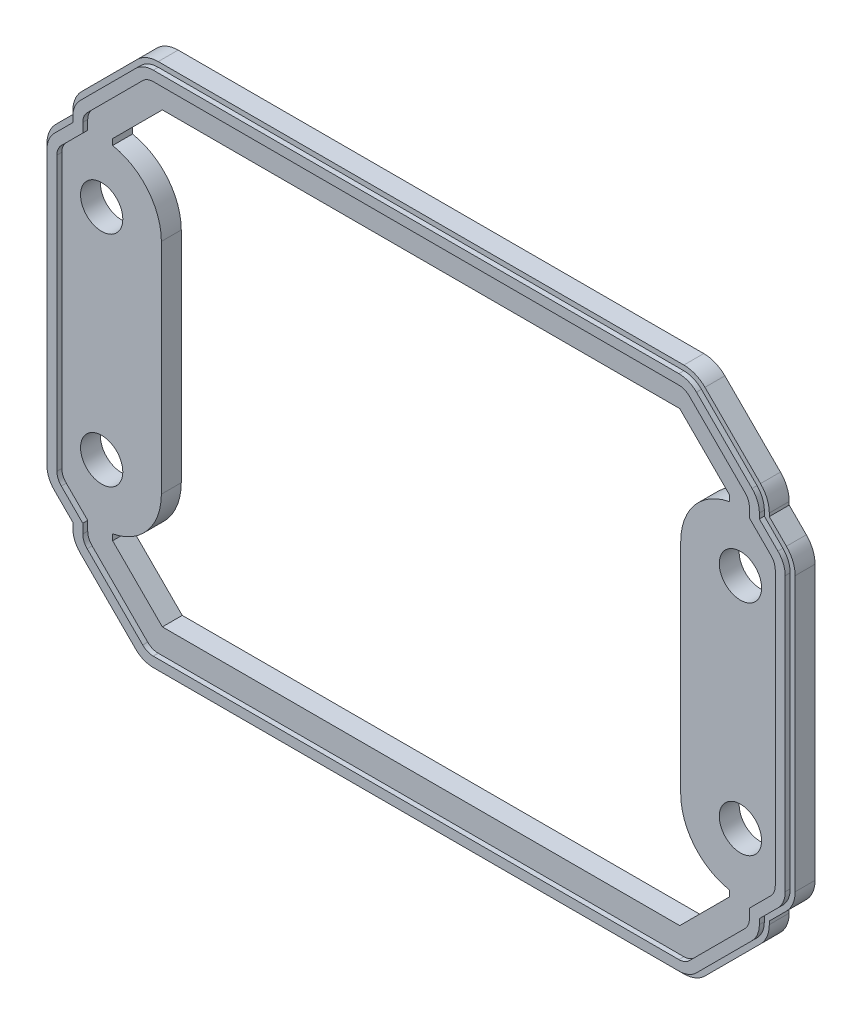
SolidWorks part; units mm, degrees
ref_plane "Front Plane" through (0, 0, 0) normal (0, 0, 1) x (1, 0, 0)
ref_plane "Top Plane" through (0, 0, 0) normal (0, 1, 0) x (1, 0, 0)
ref_plane "Right Plane" through (0, 0, 0) normal (1, 0, 0) x (0, 0, -1)
sketch "Sketch1" plane through (0, 0, 0) normal (0, 0, 1) x (1, 0, 0)
  line L12 (-1.6569, 49) -> (-53.6569, 49)
  line L13 (3.3431, 44) -> (-1.6569, 49)
  line L14 (3.3431, 43.3983) -> (3.3431, 44)
  line L15 (-1.5569, 15.5) -> (-1.5569, 37.5)
  line L16 (-64.3782, 10.6213) -> (-62.6569, 8.9)
  line L17 (-62.6569, 8.9) -> (-62.6569, 8.5858)
  line L18 (-61.7782, 6.4645) -> (-56.1924, 0.8787)
  line L19 (-54.0711, 0) -> (-1.2426, 0)
  line L20 (0.8787, 0.8787) -> (6.4645, 6.4645)
  line L21 (7.3431, 8.5858) -> (7.3431, 8.9)
  line L22 (7.3431, 8.9) -> (9.0645, 10.6213)
  line L23 (9.9431, 12.7426) -> (9.9431, 40.2574)
  line L24 (9.0645, 42.3787) -> (7.3431, 44.1)
  line L25 (7.3431, 44.1) -> (7.3431, 44.4142)
  line L26 (6.4645, 46.5355) -> (0.8787, 52.1213)
  line L27 (-1.2426, 53) -> (-54.0711, 53)
  line L28 (-56.1924, 52.1213) -> (-61.7782, 46.5355)
  line L29 (-62.6569, 44.4142) -> (-62.6569, 44.1)
  line L30 (-62.6569, 44.1) -> (-64.3782, 42.3787)
  line L31 (-65.2569, 40.2574) -> (-65.2569, 12.7426)
  line L32 (-64.3782, 10.6213) -> (-62.6569, 8.9)
  line L33 (-62.6569, 8.9) -> (-62.6569, 8.5858)
  line L34 (-61.7782, 6.4645) -> (-56.1924, 0.8787)
  line L35 (-54.0711, 0) -> (-1.2426, 0)
  line L36 (0.8787, 0.8787) -> (6.4645, 6.4645)
  line L37 (7.3431, 8.5858) -> (7.3431, 8.9)
  line L38 (7.3431, 8.9) -> (9.0645, 10.6213)
  line L39 (9.9431, 12.7426) -> (9.9431, 40.2574)
  line L40 (9.0645, 42.3787) -> (7.3431, 44.1)
  line L41 (7.3431, 44.1) -> (7.3431, 44.4142)
  line L42 (6.4645, 46.5355) -> (0.8787, 52.1213)
  line L43 (-1.2426, 53) -> (-54.0711, 53)
  line L44 (-56.1924, 52.1213) -> (-61.7782, 46.5355)
  line L45 (-62.6569, 44.4142) -> (-62.6569, 44.1)
  line L46 (-62.6569, 44.1) -> (-64.3782, 42.3787)
  line L47 (-65.2569, 40.2574) -> (-65.2569, 12.7426)
  line L48 (3.3431, 9) -> (3.3431, 9.6017)
  line L49 (-1.6569, 4) -> (3.3431, 9)
  line L50 (-53.6569, 4) -> (-1.6569, 4)
  line L51 (-58.6569, 9) -> (-53.6569, 4)
  line L52 (-58.6569, 9.6017) -> (-58.6569, 9)
  line L53 (-53.7569, 37.5) -> (-53.7569, 15.5)
  line L54 (-58.6569, 44) -> (-58.6569, 43.3983)
  line L55 (-53.6569, 49) -> (-58.6569, 44)
  line L56 (-1.6569, 49) -> (-53.6569, 49)
  line L57 (3.3431, 44) -> (-1.6569, 49)
  line L58 (3.3431, 43.3983) -> (3.3431, 44)
  line L59 (-1.5569, 15.5) -> (-1.5569, 37.5)
  line L60 (3.3431, 9) -> (3.3431, 9.6017)
  line L61 (-1.6569, 4) -> (3.3431, 9)
  line L62 (-53.6569, 4) -> (-1.6569, 4)
  line L63 (-58.6569, 9) -> (-53.6569, 4)
  line L64 (-58.6569, 9.6017) -> (-58.6569, 9)
  line L65 (-53.7569, 37.5) -> (-53.7569, 15.5)
  line L66 (-58.6569, 44) -> (-58.6569, 43.3983)
  line L67 (-53.6569, 49) -> (-58.6569, 44)
  circle A1 centre (4.4431, 37.5) radius 2.125
  circle A2 centre (4.4431, 37.5) radius 2.125
  circle A3 centre (-59.7569, 37.5) radius 2.125
  circle A4 centre (-59.7569, 37.5) radius 2.125
  circle A5 centre (-59.7569, 15.5) radius 2.125
  circle A6 centre (-59.7569, 15.5) radius 2.125
  circle A7 centre (4.4431, 15.5) radius 2.125
  circle A8 centre (4.4431, 15.5) radius 2.125
  arc A12 (3.3431, 43.3983) -> (-1.5569, 37.5) centre (4.4431, 37.5) ccw
  arc A13 (-1.5569, 15.5) -> (3.3431, 9.6017) centre (4.4431, 15.5) ccw
  arc A14 (-58.6569, 9.6017) -> (-53.7569, 15.5) centre (-59.7569, 15.5) ccw
  arc A15 (-53.7569, 37.5) -> (-58.6569, 43.3983) centre (-59.7569, 37.5) ccw
  arc A16 (3.3431, 43.3983) -> (-1.5569, 37.5) centre (4.4431, 37.5) ccw
  arc A17 (-1.5569, 15.5) -> (3.3431, 9.6017) centre (4.4431, 15.5) ccw
  arc A18 (-58.6569, 9.6017) -> (-53.7569, 15.5) centre (-59.7569, 15.5) ccw
  arc A19 (-53.7569, 37.5) -> (-58.6569, 43.3983) centre (-59.7569, 37.5) ccw
  arc A56 (9.0645, 10.6213) -> (9.9431, 12.7426) centre (6.9431, 12.7426) ccw
  arc A57 (9.0645, 10.6213) -> (9.9431, 12.7426) centre (6.9431, 12.7426) ccw
  arc A58 (9.9431, 40.2574) -> (9.0645, 42.3787) centre (6.9431, 40.2574) ccw
  arc A59 (9.9431, 40.2574) -> (9.0645, 42.3787) centre (6.9431, 40.2574) ccw
  arc A60 (7.3431, 44.4142) -> (6.4645, 46.5355) centre (4.3431, 44.4142) ccw
  arc A61 (7.3431, 44.4142) -> (6.4645, 46.5355) centre (4.3431, 44.4142) ccw
  arc A62 (0.8787, 52.1213) -> (-1.2426, 53) centre (-1.2426, 50) ccw
  arc A63 (0.8787, 52.1213) -> (-1.2426, 53) centre (-1.2426, 50) ccw
  arc A64 (-54.0711, 53) -> (-56.1924, 52.1213) centre (-54.0711, 50) ccw
  arc A65 (-54.0711, 53) -> (-56.1924, 52.1213) centre (-54.0711, 50) ccw
  arc A66 (-61.7782, 46.5355) -> (-62.6569, 44.4142) centre (-59.6569, 44.4142) ccw
  arc A67 (-61.7782, 46.5355) -> (-62.6569, 44.4142) centre (-59.6569, 44.4142) ccw
  arc A68 (-64.3782, 42.3787) -> (-65.2569, 40.2574) centre (-62.2569, 40.2574) ccw
  arc A69 (-64.3782, 42.3787) -> (-65.2569, 40.2574) centre (-62.2569, 40.2574) ccw
  arc A70 (-65.2569, 12.7426) -> (-64.3782, 10.6213) centre (-62.2569, 12.7426) ccw
  arc A71 (-65.2569, 12.7426) -> (-64.3782, 10.6213) centre (-62.2569, 12.7426) ccw
  arc A72 (-62.6569, 8.5858) -> (-61.7782, 6.4645) centre (-59.6569, 8.5858) ccw
  arc A73 (-62.6569, 8.5858) -> (-61.7782, 6.4645) centre (-59.6569, 8.5858) ccw
  arc A74 (-56.1924, 0.8787) -> (-54.0711, 0) centre (-54.0711, 3) ccw
  arc A75 (-56.1924, 0.8787) -> (-54.0711, 0) centre (-54.0711, 3) ccw
  arc A76 (-1.2426, 0) -> (0.8787, 0.8787) centre (-1.2426, 3) ccw
  arc A77 (-1.2426, 0) -> (0.8787, 0.8787) centre (-1.2426, 3) ccw
  arc A78 (6.4645, 6.4645) -> (7.3431, 8.5858) centre (4.3431, 8.5858) ccw
  arc A79 (6.4645, 6.4645) -> (7.3431, 8.5858) centre (4.3431, 8.5858) ccw
  dimension "D1" = 0
  dimension "D2" = 0
  dimension "D3" = 0
  dimension "D4" = 0
  dimension "D5" = 0
  dimension "D6" = 0
extrude "Boss-Extrude1" add sketch "Sketch1" along normal blind 2
sketch "Sketch2" plane through (0, 0, 2) normal (0, 0, 1) x (1, 0, 0)
  line L58 (-62.1569, 9.1071) -> (-62.1569, 8.5858)
  line L59 (-61.4246, 6.818) -> (-55.8388, 1.2322)
  line L60 (-54.0711, 0.5) -> (-1.2426, 0.5)
  line L61 (0.5251, 1.2322) -> (6.1109, 6.818)
  line L62 (6.8431, 8.5858) -> (6.8431, 9.1071)
  line L63 (6.8431, 9.1071) -> (8.7109, 10.9749)
  line L64 (9.4431, 12.7426) -> (9.4431, 40.2574)
  line L65 (8.7109, 42.0251) -> (6.8431, 43.8929)
  line L66 (6.8431, 43.8929) -> (6.8431, 44.4142)
  line L67 (6.1109, 46.182) -> (0.5251, 51.7678)
  line L68 (-1.2426, 52.5) -> (-54.0711, 52.5)
  line L69 (-55.8388, 51.7678) -> (-61.4246, 46.182)
  line L70 (-62.1569, 44.4142) -> (-62.1569, 43.8929)
  line L71 (-62.1569, 43.8929) -> (-64.0246, 42.0251)
  line L72 (-64.7569, 40.2574) -> (-64.7569, 12.7426)
  line L73 (-64.0246, 10.9749) -> (-62.1569, 9.1071)
  line L74 (-62.1569, 9.1071) -> (-62.1569, 8.5858)
  line L75 (-61.4246, 6.818) -> (-55.8388, 1.2322)
  line L76 (-54.0711, 0.5) -> (-1.2426, 0.5)
  line L77 (0.5251, 1.2322) -> (6.1109, 6.818)
  line L78 (6.8431, 8.5858) -> (6.8431, 9.1071)
  line L79 (6.8431, 9.1071) -> (8.7109, 10.9749)
  line L80 (9.4431, 12.7426) -> (9.4431, 40.2574)
  line L81 (8.7109, 42.0251) -> (6.8431, 43.8929)
  line L82 (6.8431, 43.8929) -> (6.8431, 44.4142)
  line L83 (6.1109, 46.182) -> (0.5251, 51.7678)
  line L84 (-1.2426, 52.5) -> (-54.0711, 52.5)
  line L85 (-55.8388, 51.7678) -> (-61.4246, 46.182)
  line L86 (-62.1569, 44.4142) -> (-62.1569, 43.8929)
  line L87 (-62.1569, 43.8929) -> (-64.0246, 42.0251)
  line L88 (-64.7569, 40.2574) -> (-64.7569, 12.7426)
  line L89 (-64.0246, 10.9749) -> (-62.1569, 9.1071)
  line L111 (-61.1569, 9.5213) -> (-61.1569, 8.5858)
  line L112 (-60.7175, 7.5251) -> (-55.1317, 1.9393)
  line L113 (-54.0711, 1.5) -> (-1.2426, 1.5)
  line L114 (-0.182, 1.9393) -> (5.4038, 7.5251)
  line L115 (5.8431, 8.5858) -> (5.8431, 9.5213)
  line L116 (5.8431, 9.5213) -> (8.0038, 11.682)
  line L117 (8.4431, 12.7426) -> (8.4431, 40.2574)
  line L118 (8.0038, 41.318) -> (5.8431, 43.4787)
  line L119 (5.8431, 43.4787) -> (5.8431, 44.4142)
  line L120 (5.4038, 45.4749) -> (-0.182, 51.0607)
  line L121 (-1.2426, 51.5) -> (-54.0711, 51.5)
  line L122 (-55.1317, 51.0607) -> (-60.7175, 45.4749)
  line L123 (-61.1569, 44.4142) -> (-61.1569, 43.4787)
  line L124 (-61.1569, 43.4787) -> (-63.3175, 41.318)
  line L125 (-63.7569, 40.2574) -> (-63.7569, 12.7426)
  line L126 (-63.3175, 11.682) -> (-61.1569, 9.5213)
  line L127 (-61.1569, 9.5213) -> (-61.1569, 8.5858)
  line L128 (-60.7175, 7.5251) -> (-55.1317, 1.9393)
  line L129 (-54.0711, 1.5) -> (-1.2426, 1.5)
  line L130 (-0.182, 1.9393) -> (5.4038, 7.5251)
  line L131 (5.8431, 8.5858) -> (5.8431, 9.5213)
  line L132 (5.8431, 9.5213) -> (8.0038, 11.682)
  line L133 (8.4431, 12.7426) -> (8.4431, 40.2574)
  line L134 (8.0038, 41.318) -> (5.8431, 43.4787)
  line L135 (5.8431, 43.4787) -> (5.8431, 44.4142)
  line L136 (5.4038, 45.4749) -> (-0.182, 51.0607)
  line L137 (-1.2426, 51.5) -> (-54.0711, 51.5)
  line L138 (-55.1317, 51.0607) -> (-60.7175, 45.4749)
  line L139 (-61.1569, 44.4142) -> (-61.1569, 43.4787)
  line L140 (-61.1569, 43.4787) -> (-63.3175, 41.318)
  line L141 (-63.7569, 40.2574) -> (-63.7569, 12.7426)
  line L142 (-63.3175, 11.682) -> (-61.1569, 9.5213)
  arc A30 (-62.1569, 8.5858) -> (-61.4246, 6.818) centre (-59.6569, 8.5858) ccw
  arc A31 (-55.8388, 1.2322) -> (-54.0711, 0.5) centre (-54.0711, 3) ccw
  arc A32 (-1.2426, 0.5) -> (0.5251, 1.2322) centre (-1.2426, 3) ccw
  arc A33 (6.1109, 6.818) -> (6.8431, 8.5858) centre (4.3431, 8.5858) ccw
  arc A34 (8.7109, 10.9749) -> (9.4431, 12.7426) centre (6.9431, 12.7426) ccw
  arc A35 (9.4431, 40.2574) -> (8.7109, 42.0251) centre (6.9431, 40.2574) ccw
  arc A36 (6.8431, 44.4142) -> (6.1109, 46.182) centre (4.3431, 44.4142) ccw
  arc A37 (0.5251, 51.7678) -> (-1.2426, 52.5) centre (-1.2426, 50) ccw
  arc A38 (-54.0711, 52.5) -> (-55.8388, 51.7678) centre (-54.0711, 50) ccw
  arc A39 (-61.4246, 46.182) -> (-62.1569, 44.4142) centre (-59.6569, 44.4142) ccw
  arc A40 (-64.0246, 42.0251) -> (-64.7569, 40.2574) centre (-62.2569, 40.2574) ccw
  arc A41 (-64.7569, 12.7426) -> (-64.0246, 10.9749) centre (-62.2569, 12.7426) ccw
  arc A42 (-62.1569, 8.5858) -> (-61.4246, 6.818) centre (-59.6569, 8.5858) ccw
  arc A43 (-55.8388, 1.2322) -> (-54.0711, 0.5) centre (-54.0711, 3) ccw
  arc A44 (-1.2426, 0.5) -> (0.5251, 1.2322) centre (-1.2426, 3) ccw
  arc A45 (6.1109, 6.818) -> (6.8431, 8.5858) centre (4.3431, 8.5858) ccw
  arc A46 (8.7109, 10.9749) -> (9.4431, 12.7426) centre (6.9431, 12.7426) ccw
  arc A47 (9.4431, 40.2574) -> (8.7109, 42.0251) centre (6.9431, 40.2574) ccw
  arc A48 (6.8431, 44.4142) -> (6.1109, 46.182) centre (4.3431, 44.4142) ccw
  arc A49 (0.5251, 51.7678) -> (-1.2426, 52.5) centre (-1.2426, 50) ccw
  arc A50 (-54.0711, 52.5) -> (-55.8388, 51.7678) centre (-54.0711, 50) ccw
  arc A51 (-61.4246, 46.182) -> (-62.1569, 44.4142) centre (-59.6569, 44.4142) ccw
  arc A52 (-64.0246, 42.0251) -> (-64.7569, 40.2574) centre (-62.2569, 40.2574) ccw
  arc A53 (-64.7569, 12.7426) -> (-64.0246, 10.9749) centre (-62.2569, 12.7426) ccw
  arc A69 (-61.1569, 8.5858) -> (-60.7175, 7.5251) centre (-59.6569, 8.5858) ccw
  arc A70 (-55.1317, 1.9393) -> (-54.0711, 1.5) centre (-54.0711, 3) ccw
  arc A71 (-1.2426, 1.5) -> (-0.182, 1.9393) centre (-1.2426, 3) ccw
  arc A72 (5.4038, 7.5251) -> (5.8431, 8.5858) centre (4.3431, 8.5858) ccw
  arc A73 (8.0038, 11.682) -> (8.4431, 12.7426) centre (6.9431, 12.7426) ccw
  arc A74 (8.4431, 40.2574) -> (8.0038, 41.318) centre (6.9431, 40.2574) ccw
  arc A75 (5.8431, 44.4142) -> (5.4038, 45.4749) centre (4.3431, 44.4142) ccw
  arc A76 (-0.182, 51.0607) -> (-1.2426, 51.5) centre (-1.2426, 50) ccw
  arc A77 (-54.0711, 51.5) -> (-55.1317, 51.0607) centre (-54.0711, 50) ccw
  arc A78 (-60.7175, 45.4749) -> (-61.1569, 44.4142) centre (-59.6569, 44.4142) ccw
  arc A79 (-63.3175, 41.318) -> (-63.7569, 40.2574) centre (-62.2569, 40.2574) ccw
  arc A80 (-63.7569, 12.7426) -> (-63.3175, 11.682) centre (-62.2569, 12.7426) ccw
  arc A81 (-61.1569, 8.5858) -> (-60.7175, 7.5251) centre (-59.6569, 8.5858) ccw
  arc A82 (-55.1317, 1.9393) -> (-54.0711, 1.5) centre (-54.0711, 3) ccw
  arc A83 (-1.2426, 1.5) -> (-0.182, 1.9393) centre (-1.2426, 3) ccw
  arc A84 (5.4038, 7.5251) -> (5.8431, 8.5858) centre (4.3431, 8.5858) ccw
  arc A85 (8.0038, 11.682) -> (8.4431, 12.7426) centre (6.9431, 12.7426) ccw
  arc A86 (8.4431, 40.2574) -> (8.0038, 41.318) centre (6.9431, 40.2574) ccw
  arc A87 (5.8431, 44.4142) -> (5.4038, 45.4749) centre (4.3431, 44.4142) ccw
  arc A88 (-0.182, 51.0607) -> (-1.2426, 51.5) centre (-1.2426, 50) ccw
  arc A89 (-54.0711, 51.5) -> (-55.1317, 51.0607) centre (-54.0711, 50) ccw
  arc A90 (-60.7175, 45.4749) -> (-61.1569, 44.4142) centre (-59.6569, 44.4142) ccw
  arc A91 (-63.3175, 41.318) -> (-63.7569, 40.2574) centre (-62.2569, 40.2574) ccw
  arc A92 (-63.7569, 12.7426) -> (-63.3175, 11.682) centre (-62.2569, 12.7426) ccw
  point P21 (-62.1569, 44.4142)
  point P27 (0, 0)
  dimension "D1" = 0.5
  dimension "D2" = 1.5
extrude "Boss-Extrude2" add sketch "Sketch2" along normal blind 0.5
